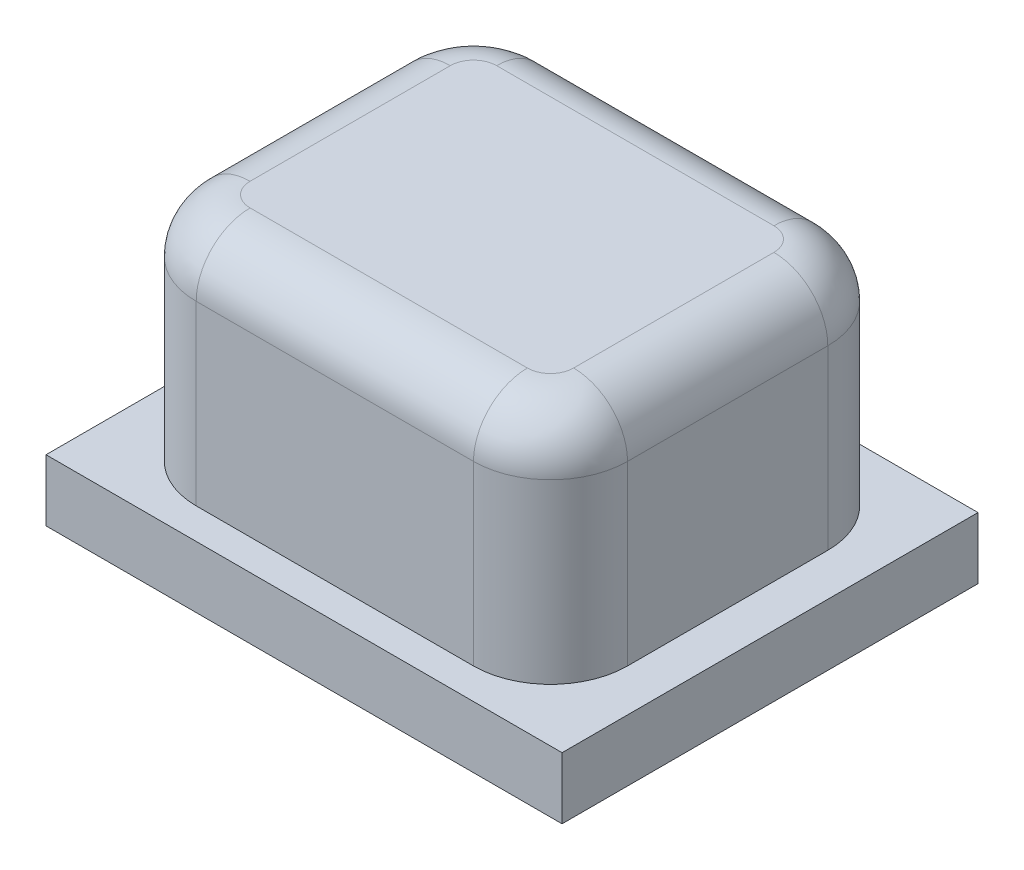
SolidWorks part; units mm, degrees
ref_plane "前视基准面" through (0, 0, 0) normal (0, 0, 1) x (1, 0, 0)
ref_plane "上视基准面" through (0, 0, 0) normal (0, 1, 0) x (1, 0, 0)
ref_plane "右视基准面" through (0, 0, 0) normal (1, 0, 0) x (0, 0, -1)
sketch "草图1" plane through (0, 0, 0) normal (0, 1, 0) x (1, 0, 0)
  line L1 (-1.8, -2.3) -> (1.8, -2.3)
  line L2 (-2.8, -1.3) -> (-2.8, 1.3)
  line L3 (-1.8, 2.3) -> (1.8, 2.3)
  line L4 (2.8, -1.3) -> (2.8, 1.3)
  line L5 (-2.8, -2.3) -> (2.8, 2.3) construction
  line L6 (-2.8, 2.3) -> (2.8, -2.3) construction
  arc A0 (1.8, -2.3) -> (2.8, -1.3) centre (1.8, -1.3) ccw
  arc A1 (-1.8, -2.3) -> (-2.8, -1.3) centre (-1.8, -1.3) cw
  arc A2 (1.8, 2.3) -> (2.8, 1.3) centre (1.8, 1.3) cw
  arc A3 (-2.8, 1.3) -> (-1.8, 2.3) centre (-1.8, 1.3) cw
  point P0 (0, 0)
  dimension "D3" = 1
  dimension "D1" = 5.6
  dimension "D2" = 4.6
extrude "按钮柱体" add sketch "草图1" along normal blind 3
sketch "草图2" plane through (0, 0, 0) normal (0, -1, 0) x (1, 0, 0)
  line L1 (-3.35, -2.7) -> (3.35, -2.7)
  line L2 (-3.35, -2.7) -> (-3.35, 2.7)
  line L3 (-3.35, 2.7) -> (3.35, 2.7)
  line L4 (3.35, -2.7) -> (3.35, 2.7)
  line L5 (-3.35, -2.7) -> (3.35, 2.7) construction
  line L6 (-3.35, 2.7) -> (3.35, -2.7) construction
  point P0 (0, 0)
  dimension "D1" = 6.7
  dimension "D2" = 5.4
extrude "按钮底座" add sketch "草图2" along normal blind 0.8
sketch "草图3" plane through (0, -0.8, 0) normal (0, -1, 0) x (1, 0, 0)
  line L5 (-1.8, -1.8) -> (1.8, -1.8)
  line L6 (-1.8, -1.8) -> (-1.8, 1.8)
  line L7 (-1.8, 1.8) -> (1.8, 1.8)
  line L8 (1.8, -1.8) -> (1.8, 1.8)
  line L9 (-1.8, -1.8) -> (1.8, 1.8) construction
  line L10 (-1.8, 1.8) -> (1.8, -1.8) construction
  point P0 (0, 0)
  dimension "D1" = 3.6
  dimension "D2" = 3.6
extrude "底部凹槽" cut sketch "草图3" against normal blind 2.6
fillet "圆角1" radius 0.7 8 edges at (2.5071, 3, -2.0071) (2.8, 3, 0) (2.5071, 3, 2.0071) (0, 3, 2.3) (-2.5071, 3, 2.0071) (-2.8, 3, 0) (-2.5071, 3, -2.0071) (0, 3, -2.3)
